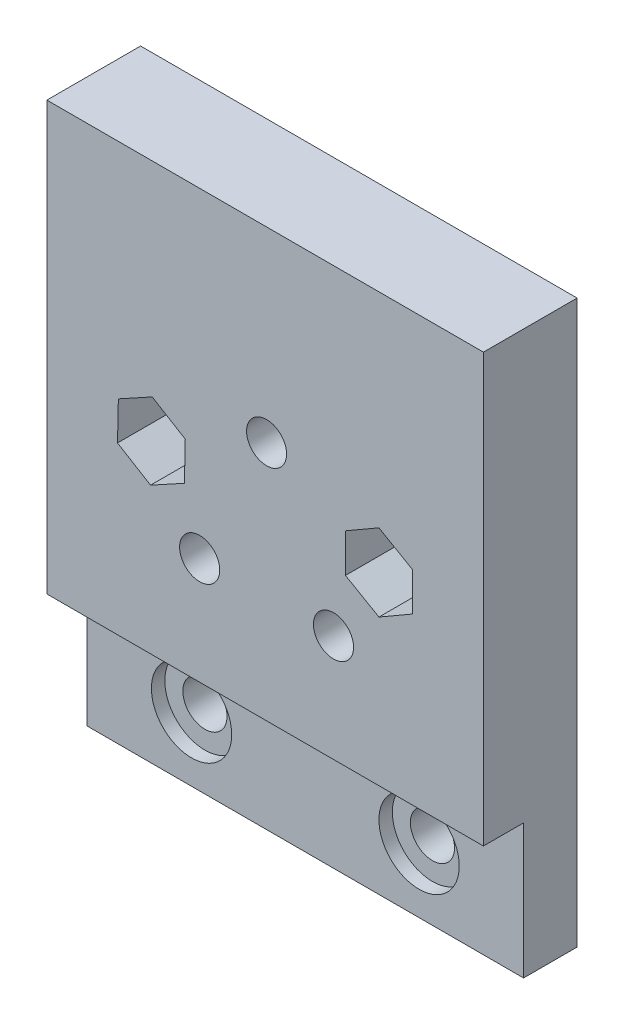
SolidWorks part; units mm, degrees
ref_plane "Přední rovina" through (0, 0, 0) normal (0, 0, 1) x (1, 0, 0)
ref_plane "Horní rovina" through (0, 0, 0) normal (0, 1, 0) x (1, 0, 0)
ref_plane "Pravá rovina" through (0, 0, 0) normal (1, 0, 0) x (0, 0, -1)
sketch "Skica1" plane through (0, 0, 0) normal (0, 0, 1) x (1, 0, 0)
  line L0 (9, -16) -> (23.6142, -12.676) construction
  line L1 (-16.3071, 27.6576) -> (16.3071, 27.6576)
  line L2 (-16.3071, 27.6576) -> (-16.3071, -14.338)
  line L3 (-16.3071, -14.338) -> (16.3071, -14.338)
  line L4 (16.3071, 27.6576) -> (16.3071, -14.338)
  line L5 (-16.3071, 27.6576) -> (16.3071, -14.338) construction
  line L6 (-16.3071, -14.338) -> (16.3071, 27.6576) construction
  circle A0 centre (-8.5, 9.5) radius 1.65
  circle A1 centre (8.5, 9.5) radius 1.65
  circle A2 centre (8.5, -9.5) radius 1.65
  circle A3 centre (-8.5, -9.5) radius 1.65
  point P0 (0, 6.6598)
  point P27 (0, -12.85)
  point P28 (0, 0)
extrude "Přidat vysunutím1" add sketch "Skica1" along normal blind 4
sketch "Skica2" plane through (0, 0, 4) normal (0, 0, 1) x (1, 0, 0)
  line L1 (-8.4373, 12.3861) -> (-10.9681, 10.9973)
  line L2 (-10.9681, 10.9973) -> (-11.0308, 8.1113)
  line L3 (-11.0308, 8.1113) -> (-8.5627, 6.6139)
  line L4 (-8.5627, 6.6139) -> (-6.0319, 8.0027)
  line L5 (-6.0319, 8.0027) -> (-5.9692, 10.8887)
  line L6 (-5.9692, 10.8887) -> (-8.4373, 12.3861)
  line L7 (8.5, 12.3868) -> (6, 10.9434)
  line L8 (6, 10.9434) -> (6, 8.0566)
  line L9 (6, 8.0566) -> (8.5, 6.6132)
  line L10 (8.5, 6.6132) -> (11, 8.0566)
  line L11 (11, 8.0566) -> (11, 10.9434)
  line L12 (11, 10.9434) -> (8.5, 12.3868)
  circle A0 centre (-8.5, 9.5) radius 2.5 construction
  circle A1 centre (8.5, 9.5) radius 2.5 construction
  dimension "D1" = 5
extrude "Odebrat vysunutím1" cut sketch "Skica2" against normal blind 3
sketch "Skica3" plane through (0, 0, 4) normal (0, 0, 1) x (1, 0, 0)
  line L0 (16.3071, -14.338) -> (16.3071, 27.6576) construction
  line L1 (-16.3071, 27.6576) -> (16.3071, 27.6576)
  line L2 (-16.3071, 27.6576) -> (-16.3071, -4.2983)
  line L3 (-16.3071, -4.2983) -> (16.3071, -4.2983)
  line L4 (16.3071, 27.6576) -> (16.3071, -4.2983)
  line L5 (-8.4373, 12.3861) -> (-10.9681, 10.9973) construction
  line L6 (-10.9681, 10.9973) -> (-11.0308, 8.1113) construction
  line L7 (-11.0308, 8.1113) -> (-8.5627, 6.6139) construction
  line L8 (-8.5627, 6.6139) -> (-6.0319, 8.0027) construction
  line L9 (-6.0319, 8.0027) -> (-5.9692, 10.8887) construction
  line L10 (-5.9692, 10.8887) -> (-8.4373, 12.3861) construction
  line L11 (11, 10.9434) -> (8.5, 12.3868) construction
  line L12 (11, 8.0566) -> (11, 10.9434) construction
  line L13 (8.5, 6.6132) -> (11, 8.0566) construction
  line L14 (6, 8.0566) -> (8.5, 6.6132) construction
  line L15 (6, 10.9434) -> (6, 8.0566) construction
  line L16 (8.5, 12.3868) -> (6, 10.9434) construction
  line L17 (-8.4373, 12.3861) -> (-10.9681, 10.9973)
  line L18 (-10.9681, 10.9973) -> (-11.0308, 8.1113)
  line L19 (-11.0308, 8.1113) -> (-8.5627, 6.6139)
  line L20 (-8.5627, 6.6139) -> (-6.0319, 8.0027)
  line L21 (-6.0319, 8.0027) -> (-5.9692, 10.8887)
  line L22 (-5.9692, 10.8887) -> (-8.4373, 12.3861)
  line L23 (11, 10.9434) -> (8.5, 12.3868)
  line L24 (11, 8.0566) -> (11, 10.9434)
  line L25 (8.5, 6.6132) -> (11, 8.0566)
  line L26 (6, 8.0566) -> (8.5, 6.6132)
  line L27 (6, 10.9434) -> (6, 8.0566)
  line L28 (8.5, 12.3868) -> (6, 10.9434)
extrude "Přidat vysunutím2" add sketch "Skica3" along normal blind 3
sketch "Skica4" plane through (0, 0, 1) normal (0, 0, 1) x (1, 0, 0)
  line L0 (-5.9692, 10.8887) -> (-8.4373, 12.3861) construction
  line L1 (-8.4373, 12.3861) -> (-10.9681, 10.9973) construction
  line L2 (-10.9681, 10.9973) -> (-11.0308, 8.1113) construction
  line L3 (-11.0308, 8.1113) -> (-8.5627, 6.6139) construction
  line L4 (-8.5627, 6.6139) -> (-6.0319, 8.0027) construction
  line L5 (-6.0319, 8.0027) -> (-5.9692, 10.8887) construction
  line L6 (11, 10.9434) -> (8.5, 12.3868) construction
  line L7 (8.5, 12.3868) -> (6, 10.9434) construction
  line L8 (6, 10.9434) -> (6, 8.0566) construction
  line L9 (6, 8.0566) -> (8.5, 6.6132) construction
  line L10 (8.5, 6.6132) -> (11, 8.0566) construction
  line L11 (11, 8.0566) -> (11, 10.9434) construction
  line L12 (-5.9692, 10.8887) -> (-8.4373, 12.3861)
  line L13 (-8.4373, 12.3861) -> (-10.9681, 10.9973)
  line L14 (-10.9681, 10.9973) -> (-11.0308, 8.1113)
  line L15 (-11.0308, 8.1113) -> (-8.5627, 6.6139)
  line L16 (-8.5627, 6.6139) -> (-6.0319, 8.0027)
  line L17 (-6.0319, 8.0027) -> (-5.9692, 10.8887)
  line L18 (11, 10.9434) -> (8.5, 12.3868)
  line L19 (8.5, 12.3868) -> (6, 10.9434)
  line L20 (6, 10.9434) -> (6, 8.0566)
  line L21 (6, 8.0566) -> (8.5, 6.6132)
  line L22 (8.5, 6.6132) -> (11, 8.0566)
  line L23 (11, 8.0566) -> (11, 10.9434)
  circle A0 centre (-8.5, 9.5) radius 1.65 construction
  circle A1 centre (8.5, 9.5) radius 1.65 construction
  circle A2 centre (-8.5, 9.5) radius 1.65
  circle A3 centre (8.5, 9.5) radius 1.65
extrude "Přidat vysunutím3" add sketch "Skica4" along normal blind 1
sketch "Skica5" plane through (0, 0, 4) normal (0, 0, 1) x (1, 0, 0)
  circle A0 centre (8.5, -9.5) radius 3
  circle A1 centre (-8.5, -9.5) radius 3
  dimension "D1" = 6
extrude "Odebrat vysunutím2" cut sketch "Skica5" against normal blind 1
sketch "Skica6" plane through (0, 0, 7) normal (0, 0, 1) x (1, 0, 0)
  circle A0 centre (5.1071, 3.7017) radius 1.5
  circle A1 centre (-4.8929, 3.7017) radius 1.5
  circle A2 centre (0.1071, 13.7017) radius 1.4955
extrude "Odebrat vysunutím3" cut sketch "Skica6" against normal up to surface (7 mm away) up to face at (0, 6.6598, 0)
sketch "Skica7" plane through (0, 0, 0) normal (0, 0, -1) x (-1, 0, 0)
  line L0 (-15.1071, 13.7017) -> (14.8929, 13.7017) construction
  circle A0 centre (4.8929, 3.7017) radius 3.25
  circle A1 centre (-5.1071, 3.7017) radius 3.25
  circle A2 centre (-0.1071, 13.7017) radius 3.25
  dimension "D1" = 6.5
extrude "Odebrat vysunutím4" cut sketch "Skica7" against normal blind 4
